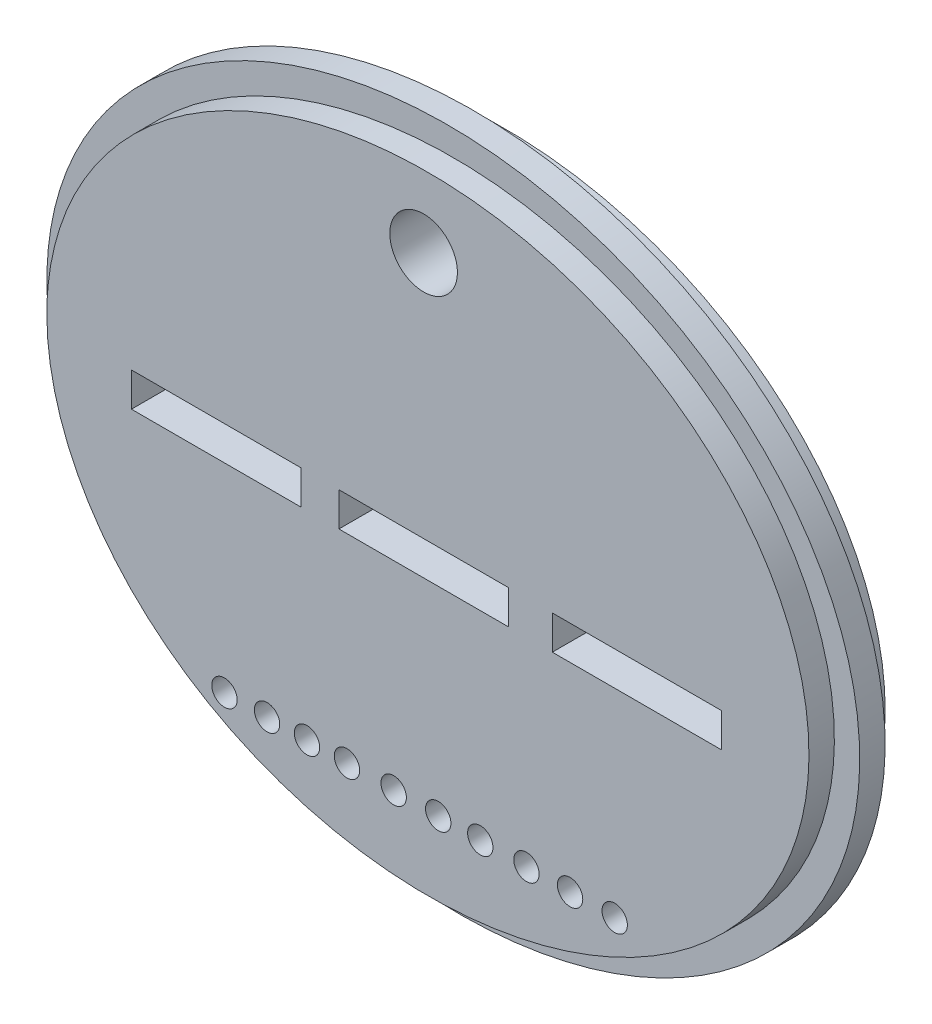
SolidWorks part; units mm, degrees
ref_plane "Front Plane" through (0, 0, 0) normal (0, 0, 1) x (1, 0, 0)
ref_plane "Top Plane" through (0, 0, 0) normal (0, 1, 0) x (1, 0, 0)
ref_plane "Right Plane" through (0, 0, 0) normal (1, 0, 0) x (0, 0, -1)
sketch "Sketch1" plane through (0, 0, 0) normal (0, 0, 1) x (1, 0, 0)
  ellipse E0 centre (0, 0) end of major axis (-47.9715, 1.6548) minor radius 40
extrude "Boss-Extrude1" add sketch "Sketch1" along normal blind 3 contours E0
sketch "Sketch2" plane through (0, 0, 3) normal (0, 0, 1) x (1, 0, 0)
  ellipse E0 centre (0, 0) end of major axis (-45, 0) minor radius 37
extrude "Boss-Extrude2" add sketch "Sketch2" along normal blind 3 and the other way blind 6
sketch "Sketch4" plane through (0, 0, 6) normal (0, 0, 1) x (1, 0, 0)
  line L0 (45, 0) -> (-45, 0) construction
  line L1 (0, 0) -> (0, -28.2262) construction
  line L2 (0, -28.2262) -> (-29.0948, -28.2262) construction
  line L3 (0, -28.2262) -> (29.0948, -28.2262) construction
  line L4 (34.6929, 34.865) -> (-45, 34.865) construction
  line L5 (34.6929, 5.3593) -> (-45, 5.3593) construction
  line L6 (34.6929, 5.3593) -> (34.6929, -17.972) construction
  line L7 (34.6929, -17.972) -> (-45, -17.972) construction
  line L8 (-45, 5.3593) -> (-45, -17.972) construction
  line L9 (34.6929, 5.3593) -> (-45, -17.972) construction
  line L10 (34.6929, -17.972) -> (-45, 5.3593) construction
  line L11 (14.6939, 34.865) -> (14.6939, -17.972) construction
  line L12 (34.6929, 8.2544) -> (14.6939, 8.4465) construction
  line L13 (14.6929, -4.739) -> (9.4928, -4.739) construction
  line L14 (34.6929, -0.7235) -> (14.6929, -0.7235)
  line L15 (34.6929, -0.7235) -> (34.6929, -4.739)
  line L16 (34.6929, -4.739) -> (14.6929, -4.739)
  line L17 (14.6929, -0.7235) -> (14.6929, -4.739)
  line L18 (34.6929, -0.7235) -> (14.6929, -4.739) construction
  line L19 (34.6929, -4.739) -> (14.6929, -0.7235) construction
  line L20 (9.4928, -4.739) -> (-10.5072, -4.739)
  line L21 (9.4928, -4.739) -> (9.4928, -0.7235)
  line L22 (9.4928, -0.7235) -> (-10.5072, -0.7235)
  line L23 (-10.5072, -4.739) -> (-10.5072, -0.7235)
  line L24 (9.4928, -4.739) -> (-10.5072, -0.7235) construction
  line L25 (9.4928, -0.7235) -> (-10.5072, -4.739) construction
  line L26 (-15.0077, -4.739) -> (-35.0077, -4.739)
  line L27 (-15.0077, -4.739) -> (-15.0077, -0.7235)
  line L28 (-15.0077, -0.7235) -> (-35.0077, -0.7235)
  line L29 (-35.0077, -4.739) -> (-35.0077, -0.7235)
  line L30 (-15.0077, -4.739) -> (-35.0077, -0.7235) construction
  line L31 (-15.0077, -0.7235) -> (-35.0077, -4.739) construction
  line L32 (-10.5072, -4.739) -> (-15.0077, -4.739) construction
  circle A0 centre (22.0581, -28.2262) radius 1.5
  circle A1 centre (16.7871, -28.2262) radius 1.5
  circle A2 centre (11.6399, -28.2262) radius 1.5
  circle A3 centre (6.186, -28.2262) radius 1.5
  circle A4 centre (1.2218, -28.2262) radius 1.5
  circle A5 centre (-4.0438, -28.2262) radius 1.5
  circle A6 centre (-9.5589, -28.2262) radius 1.5
  circle A7 centre (-14.2767, -28.2262) radius 1.5
  circle A8 centre (-18.9953, -28.2262) radius 1.5
  circle A9 centre (-24.024, -28.2262) radius 1.5
  circle A10 centre (-0.5072, 28.493) radius 3.9929
  ellipse E0 centre (0, 0) end of major axis (-45, 0) minor radius 37 construction
  point P41 (24.6929, -2.7312)
  point P46 (-0.5072, -2.7312)
  point P54 (-5.1535, -6.3063)
  point P56 (-25.0077, -2.7312)
  point P59 (-0.5072, 28.493)
extrude "Cut-Extrude1" cut sketch "Sketch4" against normal blind 14
